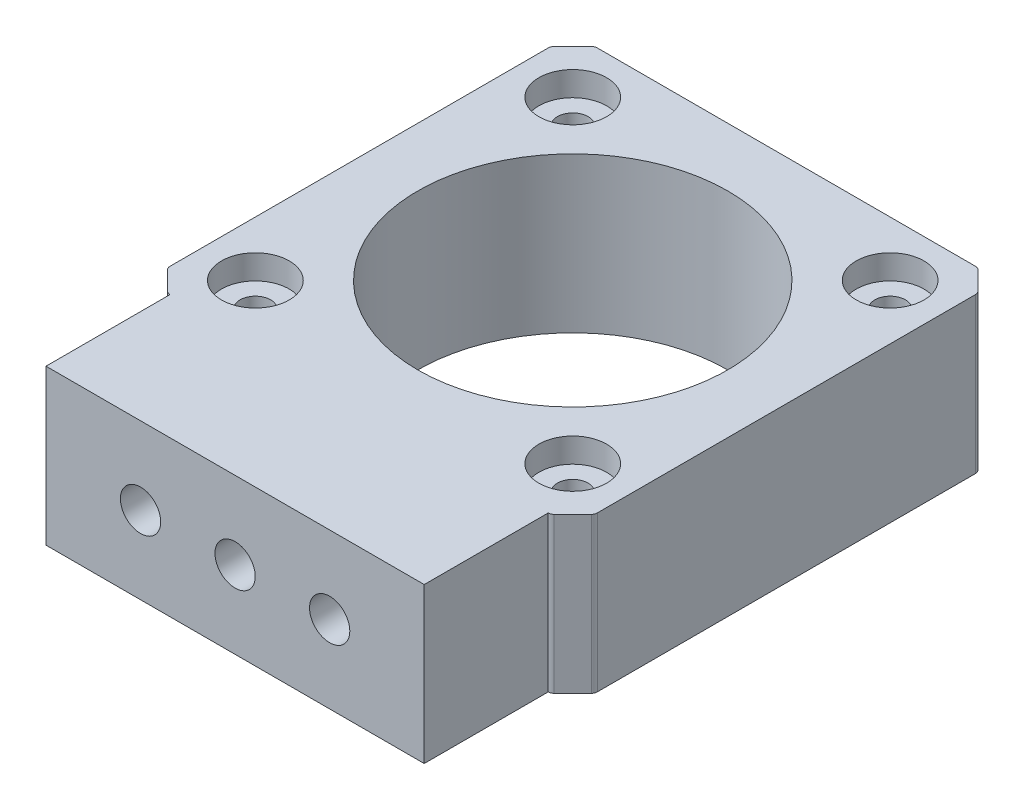
SolidWorks part; units mm, degrees
ref_plane "Front Plane" through (0, 0, 0) normal (0, 0, 1) x (1, 0, 0)
ref_plane "Top Plane" through (0, 0, 0) normal (0, 1, 0) x (1, 0, 0)
ref_plane "Right Plane" through (0, 0, 0) normal (1, 0, 0) x (0, 0, -1)
sketch "Sketch1" plane through (0, 0, 0) normal (0, 1, 0) x (1, 0, 0)
  line L0 (21.6863, 59.206) -> (23.2272, 57.6652)
  line L1 (23.3576, 57.3284) -> (23.3576, 26.3445)
  line L3 (23.2272, 26.0077) -> (21.6863, 24.4669)
  line L6 (21.3495, 24.3364) -> (-9.6343, 24.3364)
  line L7 (-9.9711, 24.4669) -> (-11.512, 26.0077)
  line L8 (-11.6424, 26.3445) -> (-11.6424, 57.3284)
  line L9 (-11.512, 57.6652) -> (-9.9711, 59.206)
  line L10 (-9.6343, 59.3364) -> (21.3495, 59.3364)
  arc A0 (23.2272, 57.6652) -> (23.3576, 57.3284) centre (22.8576, 57.3284) cw
  arc A1 (23.3576, 26.3445) -> (23.2272, 26.0077) centre (22.8576, 26.3445) cw
  arc A2 (21.6863, 24.4669) -> (21.3495, 24.3364) centre (21.3495, 24.8364) cw
  arc A4 (-9.6343, 24.3364) -> (-9.9711, 24.4669) centre (-9.6343, 24.8364) cw
  arc A5 (-11.512, 26.0077) -> (-11.6424, 26.3445) centre (-11.1424, 26.3445) cw
  arc A6 (-11.6424, 57.3284) -> (-11.512, 57.6652) centre (-11.1424, 57.3284) cw
  arc A7 (-9.6343, 59.3364) -> (-9.9711, 59.206) centre (-9.6343, 58.8364) ccw
  arc A8 (21.6863, 59.206) -> (21.3495, 59.3364) centre (21.3495, 58.8364) ccw
  circle A10 centre (5.8576, 41.8364) radius 12.7
  circle A11 centre (18.8576, 54.8364) radius 1.65
  circle A12 centre (18.8576, 28.8364) radius 1.65
  circle A13 centre (-7.1424, 54.8364) radius 1.65
  circle A14 centre (-7.1424, 28.8364) radius 1.65
  point P4 (22.9695, 20.4794)
  dimension "D1" = 25.4
  dimension "D2" = 3.3
  dimension "D3" = 3.3
  dimension "D4" = 3.3
  dimension "D5" = 3.3
extrude "Boss-Extrude1" add sketch "Sketch1" along normal blind 12.7
sketch "Sketch2" plane through (0, 0, -24.3364) normal (0, 0, 1) x (1, 0, 0)
  line L0 (5.8576, 0) -> (5.8576, 12.7) construction
  line L1 (-9.6343, 0) -> (21.3495, 0) construction
  line L2 (-9.6343, 12.7) -> (21.3495, 12.7) construction
  line L3 (-9.6343, 6.35) -> (5.8576, 6.35) construction
  line L4 (-9.6343, 12.7) -> (-9.6343, 0) construction
  line L5 (5.8576, 6.35) -> (21.3495, 6.35) construction
  line L6 (21.3495, 12.7) -> (21.3495, 0) construction
  circle A0 centre (-1.8884, 6.35) radius 1.65
  circle A1 centre (13.6036, 6.35) radius 1.65
  circle A2 centre (5.8576, 6.35) radius 1.65
  dimension "D1" = 3.3
  dimension "D2" = 3.3
  dimension "D3" = 3.3
extrude "Cut-Extrude1" cut sketch "Sketch2" against normal blind 12.7
sketch "Sketch3" plane through (0, 12.7, 0) normal (0, 1, 0) x (1, 0, 0)
  circle A0 centre (-7.1424, 54.8364) radius 2.7749
  circle A1 centre (18.8576, 54.8364) radius 2.775
  circle A2 centre (-7.1424, 28.8364) radius 2.775
  circle A3 centre (18.8576, 28.8364) radius 2.775
extrude "Cut-Extrude3" cut sketch "Sketch3" against normal blind 1.999
sketch "Sketch7" plane through (0, 10.701, 0) normal (0, 1, 0) x (1, 0, 0)
  circle A0 centre (-7.1424, 28.8364) radius 1.65
extrude "Boss-Extrude2" add sketch "Sketch7" against normal through all
sketch "Sketch8" plane through (0, 10.701, 0) normal (0, 1, 0) x (1, 0, 0)
  circle A0 centre (-7.1424, 54.8364) radius 1.65
extrude "Boss-Extrude3" add sketch "Sketch8" against normal through all
sketch "Sketch9" plane through (0, 10.701, 0) normal (0, 1, 0) x (1, 0, 0)
  circle A0 centre (18.8576, 54.8364) radius 1.65
extrude "Boss-Extrude4" add sketch "Sketch9" against normal through all
sketch "Sketch10" plane through (0, 10.701, 0) normal (0, 1, 0) x (1, 0, 0)
  circle A0 centre (18.8576, 28.8364) radius 1.65
extrude "Boss-Extrude5" add sketch "Sketch10" against normal through all
sketch "Sketch11" plane through (0, 10.701, 0) normal (0, 1, 0) x (1, 0, 0)
  circle A0 centre (-7.1424, 54.8364) radius 1.25
sketch "Sketch12" plane through (0, 10.701, 0) normal (0, 1, 0) x (1, 0, 0)
  circle A0 centre (18.8576, 54.8364) radius 1.25
  circle A1 centre (-7.1424, 28.8364) radius 1.25
  circle A2 centre (18.8576, 28.8364) radius 1.25
extrude "Cut-Extrude4" cut sketch "Sketch12" against normal blind 12.7
extrude "Cut-Extrude5" cut sketch "Sketch11" against normal blind 12.7 contours A0
sketch "Sketch17" plane through (0, 0, -24.3364) normal (0, 0, 1) x (1, 0, 0)
  line L1 (21.3495, 12.7) -> (-9.6343, 12.7)
  line L2 (21.3495, 12.7) -> (21.3495, 0)
  line L3 (21.3495, 0) -> (-9.6343, 0)
  line L4 (-9.6343, 12.7) -> (-9.6343, 0)
  line L5 (21.3495, 12.7) -> (-9.6343, 0) construction
  line L6 (21.3495, 0) -> (-9.6343, 12.7) construction
  point P4 (5.8576, 6.35)
extrude "Boss-Extrude6" add sketch "Sketch17" along normal blind 10.16
sketch "Sketch18" plane through (0, 0, -14.1764) normal (0, 0, 1) x (1, 0, 0)
  line L0 (-9.6343, 6.35) -> (5.8576, 6.35) construction
  line L1 (-9.6343, 12.7) -> (-9.6343, 0) construction
  line L2 (5.8576, 6.35) -> (21.3495, 6.35) construction
  line L3 (21.3495, 0) -> (21.3495, 12.7) construction
  circle A0 centre (-1.8884, 6.35) radius 1.65
  circle A1 centre (5.8576, 6.35) radius 1.65
  circle A2 centre (13.6036, 6.35) radius 1.65
  dimension "D1" = 3.3
  dimension "D2" = 3.3
  dimension "D3" = 3.3
extrude "Cut-Extrude6" cut sketch "Sketch18" against normal blind 24.384
